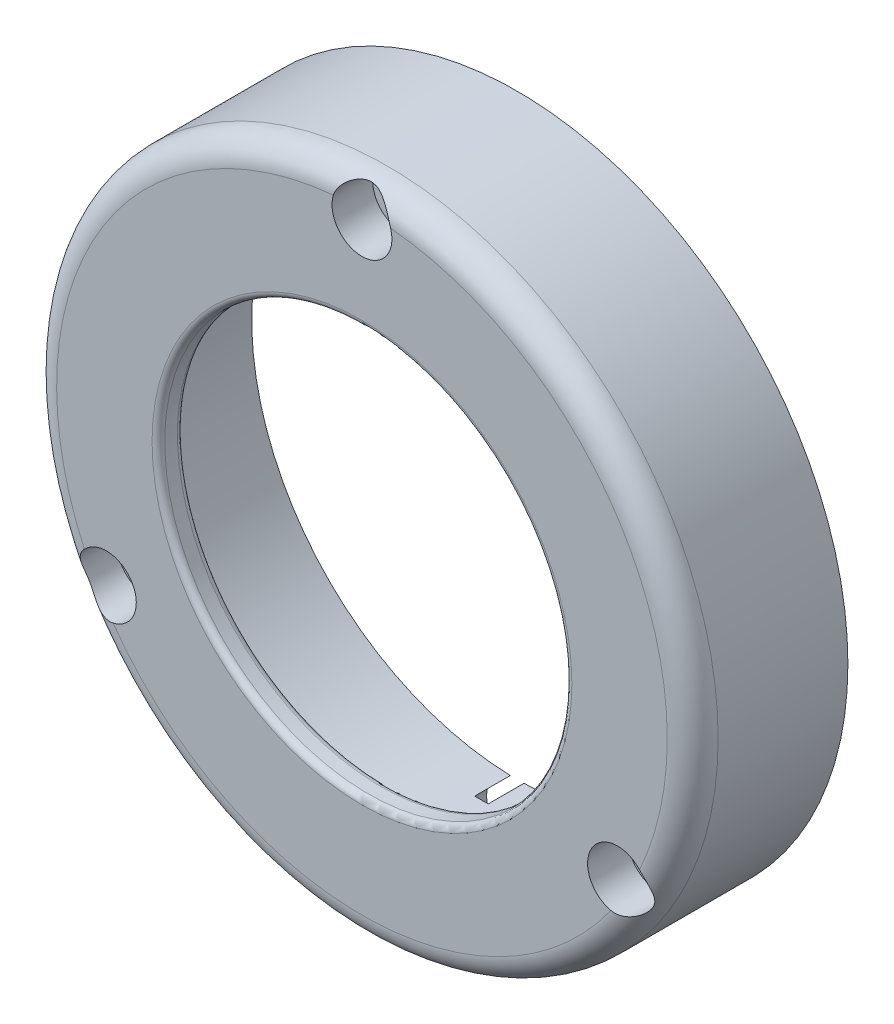
SolidWorks part; units mm, degrees
ref_plane "Front Plane" through (0, 0, 0) normal (0, 0, 1) x (1, 0, 0)
ref_plane "Top Plane" through (0, 0, 0) normal (0, 1, 0) x (1, 0, 0)
ref_plane "Right Plane" through (0, 0, 0) normal (1, 0, 0) x (0, 0, -1)
sketch "Sketch1" plane through (0, 0, 0) normal (0, 0, 1) x (1, 0, 0)
  circle A0 centre (0, 0) radius 33.126
  circle A1 centre (0, 0) radius 41.275
  dimension "D1" = 66.2521
  dimension "D2" = 82.55
extrude "Boss-Extrude1" add sketch "Sketch1" along normal blind 16.1925
sketch "Sketch2" plane through (0, 0, 16.1925) normal (0, 0, 1) x (1, 0, 0)
  circle A1 centre (0, 0) radius 25.4
  circle A2 centre (0, 0) radius 41.275 construction
  circle A3 centre (0, 0) radius 41.275
  dimension "D1" = 50.8
extrude "Boss-Extrude2" add sketch "Sketch2" along normal blind 3.175
fillet "Fillet1" radius 1.5875 1 edges at (33.126, 0, 16.1925)
fillet "Fillet2" radius 3.175 1 edges at (41.275, 0, 19.3675)
hole_wizard "M4 Clearance Hole1" positions "Sketch3" profile "Sketch4" hole size "M4" standard "ANSI Metric" end condition through all
sketch "Sketch3" plane through (0, 0, 19.3675) normal (0, 0, 1) x (1, 0, 0)
  point P0 (0, 36.83)
  dimension "D1" = 36.83
sketch "Sketch4" plane through (0, 36.83, 19.3675) normal (1, 0, 0) x (0, -1, 0)
  line L0 (0, 0) -> (0, 19.3675)
  line L1 (0, 19.3675) -> (2.15, 19.3675)
  line L2 (2.15, 19.3675) -> (2.15, 0)
  line L5 (2.15, 0) -> (0, 0)
  line L11 (0, -6.35) -> (0, 107.95) construction
  dimension "Thru Hole Dia." = 4.3
  dimension "Thru Hole Depth" = 19.3675
sketch "Sketch7" plane through (0, 0, 19.3675) normal (0, 0, 1) x (1, 0, 0)
  arc A4 (3.0665, 38.9667) -> (-3.0665, 38.9667) centre (0, 36.83) ccw
  arc A5 (-3.0665, 38.9667) -> (3.0665, 38.9667) centre (0, 36.83) ccw
  arc A6 (3.0665, 38.9667) -> (-3.0665, 38.9667) centre (0, 36.83) ccw
  arc A7 (-3.0665, 38.9667) -> (3.0665, 38.9667) centre (0, 36.83) ccw
  dimension "D1" = 1.5875
extrude "Cut-Extrude1" cut sketch "Sketch7" against normal blind 5.08
pattern_circular "CirPattern1" count 3 over 360 about axis through (0, 0, 0) along (0, 0, 1) of "M4 Clearance Hole1", "Cut-Extrude1"
fillet "Fillet3" radius 0.7937 2 edges at (25.4, 0, 16.1925) (25.4, 0, 19.3675)
sketch "Sketch8" plane through (0, 0, 0) normal (0, 0, -1) x (-1, 0, 0)
  line L0 (0, 0) -> (31.8957, 18.415) construction
  line L1 (0, 0) -> (0, 36.83) construction
  circle A1 centre (0, 0) radius 36.83 construction
  circle A2 centre (31.8957, 18.415) radius 3.81
  dimension "D2" = 7.62
  dimension "D1" = 60
extrude "Cut-Extrude2" cut sketch "Sketch8" against normal blind 4.445
pattern_circular "CirPattern2" count 3 over 360 about axis through (0, 0, 0) along (0, 0, 1) of "Cut-Extrude2"
